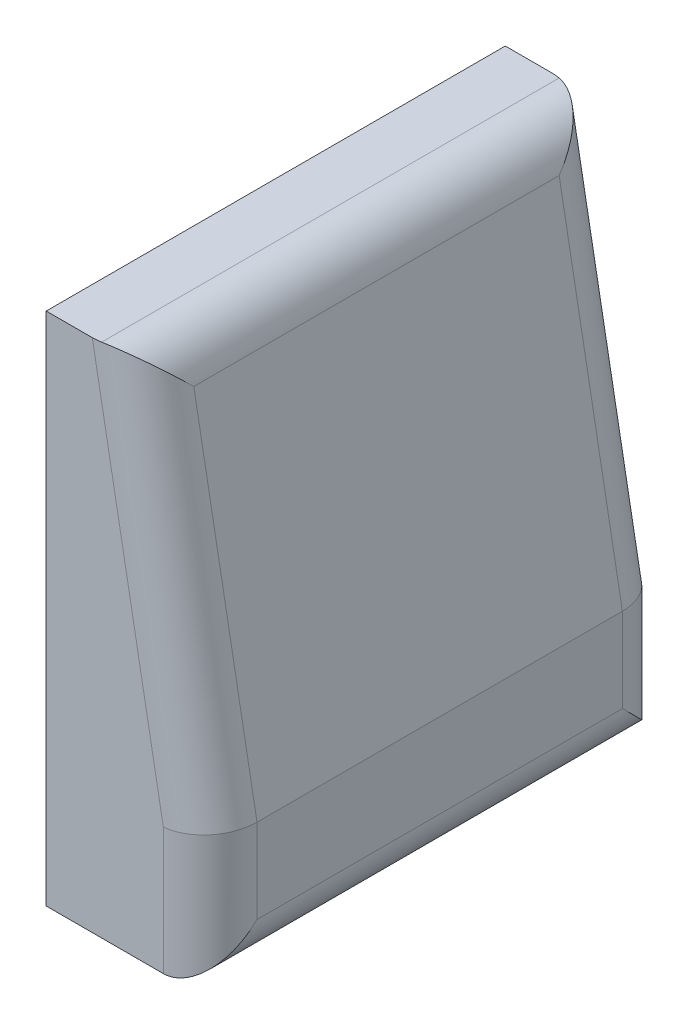
SolidWorks part; units mm, degrees
ref_plane "Front Plane" through (0, 0, 0) normal (0, 0, 1) x (1, 0, 0)
ref_plane "Top Plane" through (0, 0, 0) normal (0, 1, 0) x (1, 0, 0)
ref_plane "Right Plane" through (0, 0, 0) normal (1, 0, 0) x (0, 0, -1)
sketch "Sketch1" plane through (0, 0, 0) normal (0, 0, 1) x (1, 0, 0)
  line L0 (0, 664.4) -> (0, -435.6)
  line L1 (0, -435.6) -> (350, -435.6)
  line L2 (350, -435.6) -> (350, -155.6)
  line L3 (350, -155.6) -> (200, 664.4)
  line L4 (200, 664.4) -> (0, 664.4)
  dimension "D1" = 1100
  dimension "D2" = 200
  dimension "D3" = 350
  dimension "D4" = 280
extrude "Boss-Extrude1" add sketch "Sketch1" along normal mid plane 980
fillet "Fillet1" radius 100 6 edges at (350, -435.6, 0) (350, -295.6, 490) (350, -295.6, -490) (275, 254.4, -490) (200, 664.4, 0) (275, 254.4, 490)
